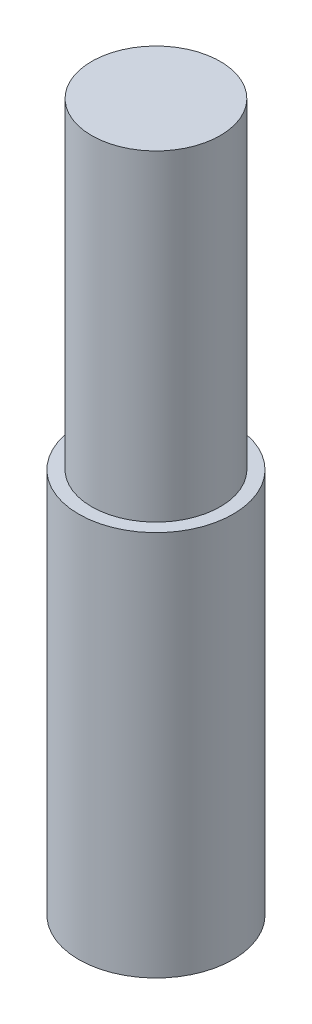
SolidWorks part; units mm, degrees
ref_plane "Front Plane" through (0, 0, 0) normal (0, 0, 1) x (1, 0, 0)
ref_plane "Top Plane" through (0, 0, 0) normal (0, 1, 0) x (1, 0, 0)
ref_plane "Right Plane" through (0, 0, 0) normal (1, 0, 0) x (0, 0, -1)
sketch "Sketch1" plane through (0, 0, 0) normal (0, 1, 0) x (1, 0, 0)
  circle A0 centre (0, 0) radius 12
extrude "Boss-Extrude1" add sketch "Sketch1" along normal blind 60
sketch "Sketch2" plane through (0, 60, 0) normal (0, 1, 0) x (1, 0, 0)
  circle A0 centre (0, 0) radius 10
extrude "Boss-Extrude2" add sketch "Sketch2" along normal blind 50
